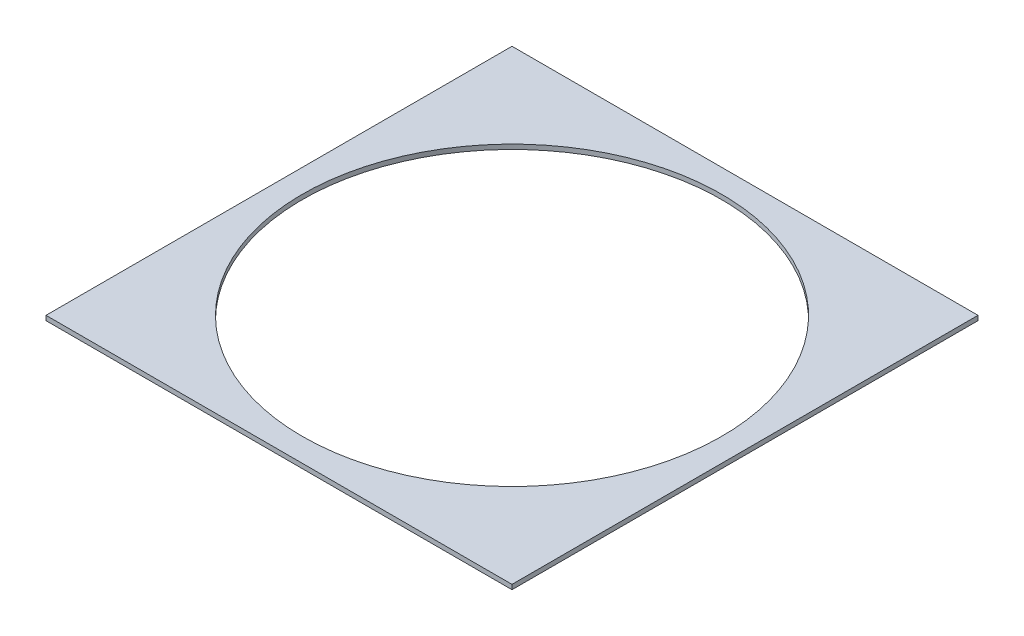
SolidWorks part; units mm, degrees
ref_plane "Front Plane" through (0, 0, 0) normal (0, 0, 1) x (1, 0, 0)
ref_plane "Top Plane" through (0, 0, 0) normal (0, 1, 0) x (1, 0, 0)
ref_plane "Right Plane" through (0, 0, 0) normal (1, 0, 0) x (0, 0, -1)
sketch "Sketch1" plane through (0, 0, 0) normal (0, 1, 0) x (1, 0, 0)
  line L1 (-63.5, -63.5) -> (63.5, -63.5)
  line L2 (-63.5, -63.5) -> (-63.5, 63.5)
  line L3 (-63.5, 63.5) -> (63.5, 63.5)
  line L4 (63.5, -63.5) -> (63.5, 63.5)
  line L5 (-63.5, -63.5) -> (63.5, 63.5) construction
  line L6 (-63.5, 63.5) -> (63.5, -63.5) construction
  point P0 (0, 0)
  dimension "D1" = 127
extrude "Boss-Extrude1" add sketch "Sketch1" along normal blind 1.27
sketch "Sketch2" plane through (0, 1.27, 0) normal (0, 1, 0) x (-1, 0, 0)
  circle A0 centre (0, 0) radius 57.15
  dimension "D1" = 114.3
extrude "Cut-Extrude1" cut sketch "Sketch2" against normal blind 1.27
